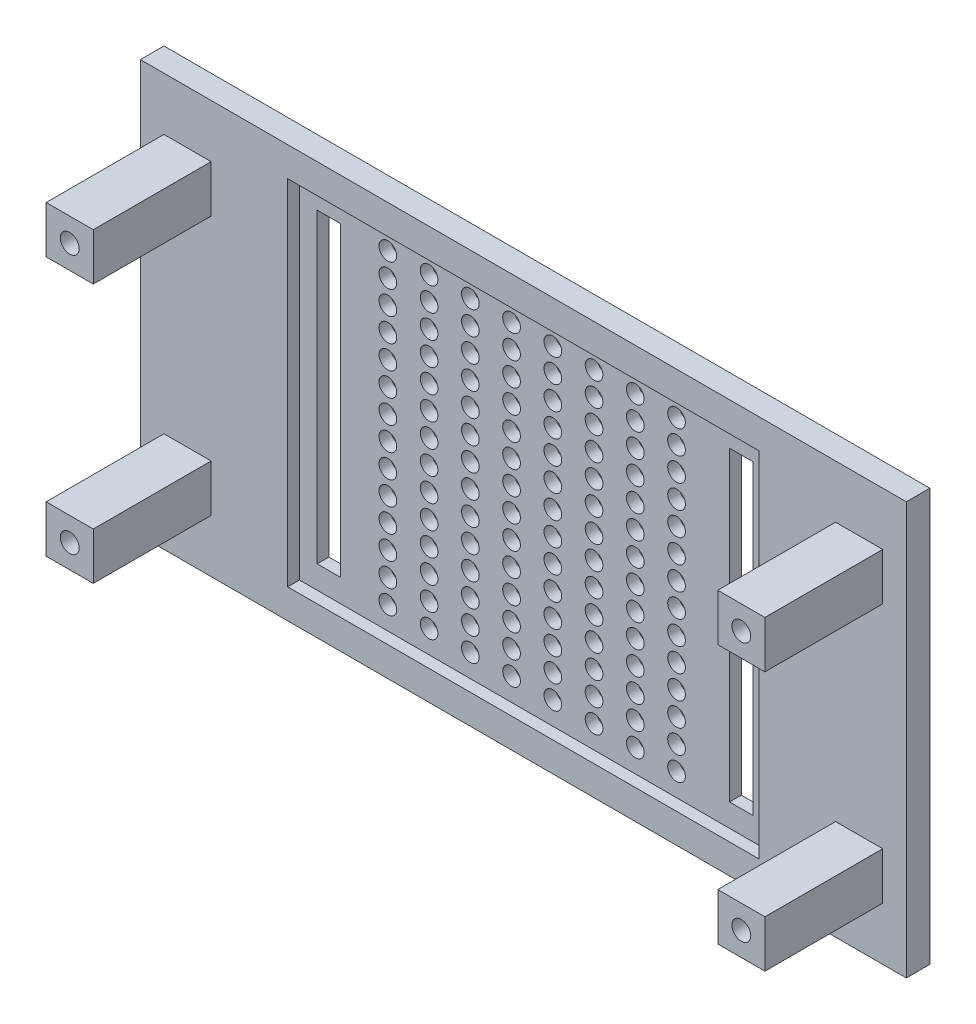
SolidWorks part; units mm, degrees
ref_plane "Front Plane" through (0, 0, 0) normal (0, 0, 1) x (1, 0, 0)
ref_plane "Top Plane" through (0, 0, 0) normal (0, 1, 0) x (1, 0, 0)
ref_plane "Right Plane" through (0, 0, 0) normal (1, 0, 0) x (0, 0, -1)
sketch "Sketch1" plane through (0, 0, 0) normal (0, 0, 1) x (1, 0, 0)
  line L1 (-32.5, 17.5) -> (32.5, 17.5)
  line L2 (-32.5, 17.5) -> (-32.5, -17.5)
  line L3 (-32.5, -17.5) -> (32.5, -17.5)
  line L4 (32.5, 17.5) -> (32.5, -17.5)
  line L5 (-32.5, 17.5) -> (32.5, -17.5) construction
  line L6 (-32.5, -17.5) -> (32.5, 17.5) construction
  point P0 (0, 0)
  point P14 (47.2615, 15.8779)
  point P15 (0, 0)
  point P16 (0, 0)
  point P17 (0, 0)
  point P18 (0, 0)
  point P19 (0, 0)
  dimension "D1" = 65
  dimension "D2" = 35
extrude "Boss-Extrude1" add sketch "Sketch1" along normal blind 2
sketch "Sketch2" plane through (0, 0, 2) normal (0, 0, 1) x (1, 0, 0)
  line L0 (32.5, 17.5) -> (-32.5, 17.5) construction
  line L1 (-30.5, 13) -> (-26.5, 13)
  line L2 (-30.5, 13) -> (-30.5, 9)
  line L3 (-30.5, 9) -> (-26.5, 9)
  line L4 (-26.5, 13) -> (-26.5, 9)
  line L5 (-30.5, 13) -> (-26.5, 9) construction
  line L6 (-30.5, 9) -> (-26.5, 13) construction
  line L7 (-30.5, -9) -> (-26.5, -9)
  line L8 (-30.5, -9) -> (-30.5, -13)
  line L9 (-30.5, -13) -> (-26.5, -13)
  line L10 (-26.5, -9) -> (-26.5, -13)
  line L11 (-30.5, -9) -> (-26.5, -13) construction
  line L12 (-30.5, -13) -> (-26.5, -9) construction
  line L13 (26.5, -9) -> (30.5, -9)
  line L14 (26.5, -9) -> (26.5, -13)
  line L15 (26.5, -13) -> (30.5, -13)
  line L16 (30.5, -9) -> (30.5, -13)
  line L17 (26.5, -9) -> (30.5, -13) construction
  line L18 (26.5, -13) -> (30.5, -9) construction
  line L19 (26.5, 13) -> (30.5, 13)
  line L20 (26.5, 13) -> (26.5, 9)
  line L21 (26.5, 9) -> (30.5, 9)
  line L22 (30.5, 13) -> (30.5, 9)
  line L23 (26.5, 13) -> (30.5, 9) construction
  line L24 (26.5, 9) -> (30.5, 13) construction
  point P0 (-28.5, 11)
  point P5 (-28.5, -11)
  point P10 (28.5, -11)
  point P15 (28.5, 11)
  point P20 (0, 0)
  point P21 (0, 0)
  point P22 (0, 0)
  point P23 (0, 0)
  point P24 (0, 0)
  dimension "D1" = 4
  dimension "D2" = 4
  dimension "D3" = 4
  dimension "D4" = 4
  dimension "D5" = 4
  dimension "D6" = 4
  dimension "D7" = 4
  dimension "D8" = 6.5
  dimension "D9" = 22
  dimension "D10" = 57
  dimension "D11" = 4
extrude "Boss-Extrude2" add sketch "Sketch2" along normal blind 10
sketch "Sketch3" plane through (0, 0, 12) normal (0, 0, 1) x (1, 0, 0)
  circle A0 centre (28.5, -11) radius 0.8
  circle A1 centre (28.5, 11) radius 0.8
  circle A2 centre (-28.5, -11) radius 0.8
  circle A3 centre (-28.5, 11) radius 0.8
  dimension "D1" = 1.6
  dimension "D2" = 1.6
  dimension "D3" = 1.6
  dimension "D4" = 1.6
extrude "Cut-Extrude1" cut sketch "Sketch3" against normal blind 5
sketch "Sketch4" plane through (0, 0, 2) normal (0, 0, 1) x (1, 0, 0)
  line L1 (-18.5, 12.9389) -> (-16.5, 12.9389)
  line L2 (-18.5, 12.9389) -> (-18.5, -13.0611)
  line L3 (-18.5, -13.0611) -> (-16.5, -13.0611)
  line L4 (-16.5, 12.9389) -> (-16.5, -13.0611)
  line L5 (-18.5, 12.9389) -> (-16.5, -13.0611) construction
  line L6 (-18.5, -13.0611) -> (-16.5, 12.9389) construction
  line L7 (16.5, 12.9389) -> (18.5, 12.9389)
  line L8 (16.5, 12.9389) -> (16.5, -13.0611)
  line L9 (16.5, -13.0611) -> (18.5, -13.0611)
  line L10 (18.5, 12.9389) -> (18.5, -13.0611)
  line L11 (16.5, 12.9389) -> (18.5, -13.0611) construction
  line L12 (16.5, -13.0611) -> (18.5, 12.9389) construction
  circle A0 centre (-12.5, 12.9389) radius 0.75
  circle A1 centre (-12.5, 10.9389) radius 0.75
  circle A2 centre (-12.5, 8.9389) radius 0.75
  circle A3 centre (-12.5, 6.9389) radius 0.75
  circle A4 centre (-12.5, 4.9389) radius 0.75
  circle A5 centre (-12.5, 2.9389) radius 0.75
  circle A6 centre (-12.5, 0.9389) radius 0.75
  circle A7 centre (-12.5, -1.0611) radius 0.75
  circle A8 centre (-12.5, -3.0611) radius 0.75
  circle A9 centre (-12.5, -5.0611) radius 0.75
  circle A10 centre (-12.5, -7.0611) radius 0.75
  circle A11 centre (-12.5, -9.0611) radius 0.75
  circle A12 centre (-12.5, -11.0611) radius 0.75
  circle A13 centre (-12.5, -13.0611) radius 0.75
  circle A14 centre (-9, 12.9389) radius 0.75
  circle A15 centre (-9, 10.9389) radius 0.75
  circle A16 centre (-9, 8.9389) radius 0.75
  circle A17 centre (-9, 6.9389) radius 0.75
  circle A18 centre (-9, 4.9389) radius 0.75
  circle A19 centre (-9, 2.9389) radius 0.75
  circle A20 centre (-9, 0.9389) radius 0.75
  circle A21 centre (-9, -1.0611) radius 0.75
  circle A22 centre (-9, -3.0611) radius 0.75
  circle A23 centre (-9, -5.0611) radius 0.75
  circle A24 centre (-9, -7.0611) radius 0.75
  circle A25 centre (-9, -9.0611) radius 0.75
  circle A26 centre (-9, -11.0611) radius 0.75
  circle A27 centre (-9, -13.0611) radius 0.75
  circle A28 centre (-5.5, 12.9389) radius 0.75
  circle A29 centre (-5.5, 10.9389) radius 0.75
  circle A30 centre (-5.5, 8.9389) radius 0.75
  circle A31 centre (-5.5, 6.9389) radius 0.75
  circle A32 centre (-5.5, 4.9389) radius 0.75
  circle A33 centre (-5.5, 2.9389) radius 0.75
  circle A34 centre (-5.5, 0.9389) radius 0.75
  circle A35 centre (-5.5, -1.0611) radius 0.75
  circle A36 centre (-5.5, -3.0611) radius 0.75
  circle A37 centre (-5.5, -5.0611) radius 0.75
  circle A38 centre (-5.5, -7.0611) radius 0.75
  circle A39 centre (-5.5, -9.0611) radius 0.75
  circle A40 centre (-5.5, -11.0611) radius 0.75
  circle A41 centre (-5.5, -13.0611) radius 0.75
  circle A42 centre (-2, 12.9389) radius 0.75
  circle A43 centre (-2, 10.9389) radius 0.75
  circle A44 centre (-2, 8.9389) radius 0.75
  circle A45 centre (-2, 6.9389) radius 0.75
  circle A46 centre (-2, 4.9389) radius 0.75
  circle A47 centre (-2, 2.9389) radius 0.75
  circle A48 centre (-2, 0.9389) radius 0.75
  circle A49 centre (-2, -1.0611) radius 0.75
  circle A50 centre (-2, -3.0611) radius 0.75
  circle A51 centre (-2, -5.0611) radius 0.75
  circle A52 centre (-2, -7.0611) radius 0.75
  circle A53 centre (-2, -9.0611) radius 0.75
  circle A54 centre (-2, -11.0611) radius 0.75
  circle A55 centre (-2, -13.0611) radius 0.75
  circle A56 centre (1.5, 12.9389) radius 0.75
  circle A57 centre (1.5, 10.9389) radius 0.75
  circle A58 centre (1.5, 8.9389) radius 0.75
  circle A59 centre (1.5, 6.9389) radius 0.75
  circle A60 centre (1.5, 4.9389) radius 0.75
  circle A61 centre (1.5, 2.9389) radius 0.75
  circle A62 centre (1.5, 0.9389) radius 0.75
  circle A63 centre (1.5, -1.0611) radius 0.75
  circle A64 centre (1.5, -3.0611) radius 0.75
  circle A65 centre (1.5, -5.0611) radius 0.75
  circle A66 centre (1.5, -7.0611) radius 0.75
  circle A67 centre (1.5, -9.0611) radius 0.75
  circle A68 centre (1.5, -11.0611) radius 0.75
  circle A69 centre (1.5, -13.0611) radius 0.75
  circle A70 centre (5, 12.9389) radius 0.75
  circle A71 centre (5, 10.9389) radius 0.75
  circle A72 centre (5, 8.9389) radius 0.75
  circle A73 centre (5, 6.9389) radius 0.75
  circle A74 centre (5, 4.9389) radius 0.75
  circle A75 centre (5, 2.9389) radius 0.75
  circle A76 centre (5, 0.9389) radius 0.75
  circle A77 centre (5, -1.0611) radius 0.75
  circle A78 centre (5, -3.0611) radius 0.75
  circle A79 centre (5, -5.0611) radius 0.75
  circle A80 centre (5, -7.0611) radius 0.75
  circle A81 centre (5, -9.0611) radius 0.75
  circle A82 centre (5, -11.0611) radius 0.75
  circle A83 centre (5, -13.0611) radius 0.75
  circle A84 centre (8.5, 12.9389) radius 0.75
  circle A85 centre (8.5, 10.9389) radius 0.75
  circle A86 centre (8.5, 8.9389) radius 0.75
  circle A87 centre (8.5, 6.9389) radius 0.75
  circle A88 centre (8.5, 4.9389) radius 0.75
  circle A89 centre (8.5, 2.9389) radius 0.75
  circle A90 centre (8.5, 0.9389) radius 0.75
  circle A91 centre (8.5, -1.0611) radius 0.75
  circle A92 centre (8.5, -3.0611) radius 0.75
  circle A93 centre (8.5, -5.0611) radius 0.75
  circle A94 centre (8.5, -7.0611) radius 0.75
  circle A95 centre (8.5, -9.0611) radius 0.75
  circle A96 centre (8.5, -11.0611) radius 0.75
  circle A97 centre (8.5, -13.0611) radius 0.75
  circle A98 centre (12, 12.9389) radius 0.75
  circle A99 centre (12, 10.9389) radius 0.75
  circle A100 centre (12, 8.9389) radius 0.75
  circle A101 centre (12, 6.9389) radius 0.75
  circle A102 centre (12, 4.9389) radius 0.75
  circle A103 centre (12, 2.9389) radius 0.75
  circle A104 centre (12, 0.9389) radius 0.75
  circle A105 centre (12, -1.0611) radius 0.75
  circle A106 centre (12, -3.0611) radius 0.75
  circle A107 centre (12, -5.0611) radius 0.75
  circle A108 centre (12, -7.0611) radius 0.75
  circle A109 centre (12, -9.0611) radius 0.75
  circle A110 centre (12, -11.0611) radius 0.75
  circle A111 centre (12, -13.0611) radius 0.75
  point P0 (-17.5, -0.0611)
  point P5 (17.5, -0.0611)
  dimension "D7" = 1.5
  dimension "D1" = 2
  dimension "D2" = 26
  dimension "D3" = 26
  dimension "D4" = 2
  dimension "D5" = 8
  dimension "D6" = 8
  dimension "D8" = 4
  dimension "D9" = 14
  dimension "D10" = 8
extrude "Cut-Extrude2" cut sketch "Sketch4" against normal blind 5
sketch "Sketch5" plane through (0, 0, 2) normal (0, 0, 1) x (1, 0, 0)
  line L1 (-20, 15) -> (20, 15)
  line L2 (-20, 15) -> (-20, -15)
  line L3 (-20, -15) -> (20, -15)
  line L4 (20, 15) -> (20, -15)
  line L5 (-20, 15) -> (20, -15) construction
  line L6 (-20, -15) -> (20, 15) construction
  point P0 (0, 0)
  dimension "D1" = 40
  dimension "D2" = 30
extrude "Cut-Extrude3" cut sketch "Sketch5" against normal blind 1
